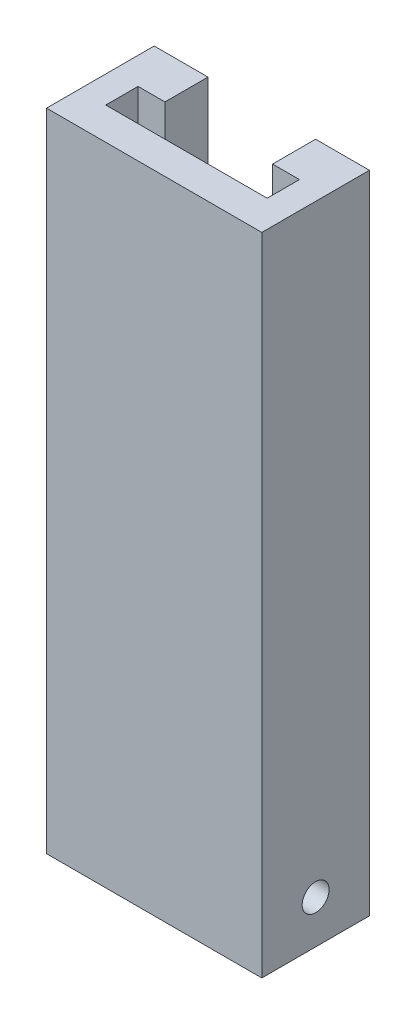
SolidWorks part; units mm, degrees
ref_plane "Płaszczyzna przednia" through (0, 0, 0) normal (0, 0, 1) x (1, 0, 0)
ref_plane "Płaszczyzna górna" through (0, 0, 0) normal (0, 1, 0) x (1, 0, 0)
ref_plane "Płaszczyzna prawa" through (0, 0, 0) normal (1, 0, 0) x (0, 0, -1)
sketch "Szkic1" plane through (0, 0, 0) normal (0, 1, 0) x (1, 0, 0)
  line L1 (-20, 10) -> (20, 10)
  line L2 (-20, 10) -> (-20, -10)
  line L3 (-20, -10) -> (20, -10)
  line L4 (20, 10) -> (20, -10)
  line L5 (-20, 10) -> (20, -10) construction
  line L6 (-20, -10) -> (20, 10) construction
  point P0 (0, 0)
  dimension "D1" = 40
  dimension "D2" = 20
extrude "Dodanie-wyciągnięcie1" add sketch "Szkic1" along normal blind 120
sketch "Szkic2" plane through (-20, 0, 0) normal (-1, 0, 0) x (0, 0, 1)
  line L0 (0, 0) -> (0, 8) construction
  circle A0 centre (0, 8) radius 2.5
  dimension "D2" = 5
  dimension "D1" = 8
extrude "Wytnij-wyciągnięcie1" cut sketch "Szkic2" against normal through all
sketch "Szkic4" plane through (0, 120, 0) normal (0, 1, 0) x (1, 0, 0)
  line L0 (0, -10) -> (0, -4) construction
  line L1 (-20, -10) -> (20, -10) construction
  line L2 (-20, 0) -> (-15, 0) construction
  line L3 (-20, 10) -> (-20, -10) construction
  line L5 (20, 0) -> (15, 0) construction
  line L6 (20, -10) -> (20, 10) construction
  line L7 (-15, -4) -> (15, -4)
  line L8 (20, 2) -> (10, 2) construction
  line L9 (20, 10) -> (-20, 10) construction
  line L10 (15, -4) -> (15, 2)
  line L11 (15, 2) -> (10, 2)
  line L12 (10, 2) -> (10, 10)
  line L13 (10, 10) -> (-10, 10)
  line L14 (-10, 10) -> (-10, 2)
  line L15 (-10, 2) -> (-15, 2)
  line L16 (-15, 2) -> (-15, -4)
  dimension "D1" = 6
  dimension "D2" = 5
  dimension "D3" = 5
  dimension "D4" = 10
  dimension "D5" = 8
  dimension "D6" = 10
  dimension "D7" = 6
  dimension "D8" = 5
  dimension "D9" = 30
  dimension "D10" = 20
  dimension "D11" = 20
extrude "Wytnij-wyciągnięcie2" cut sketch "Szkic4" against normal blind 104
